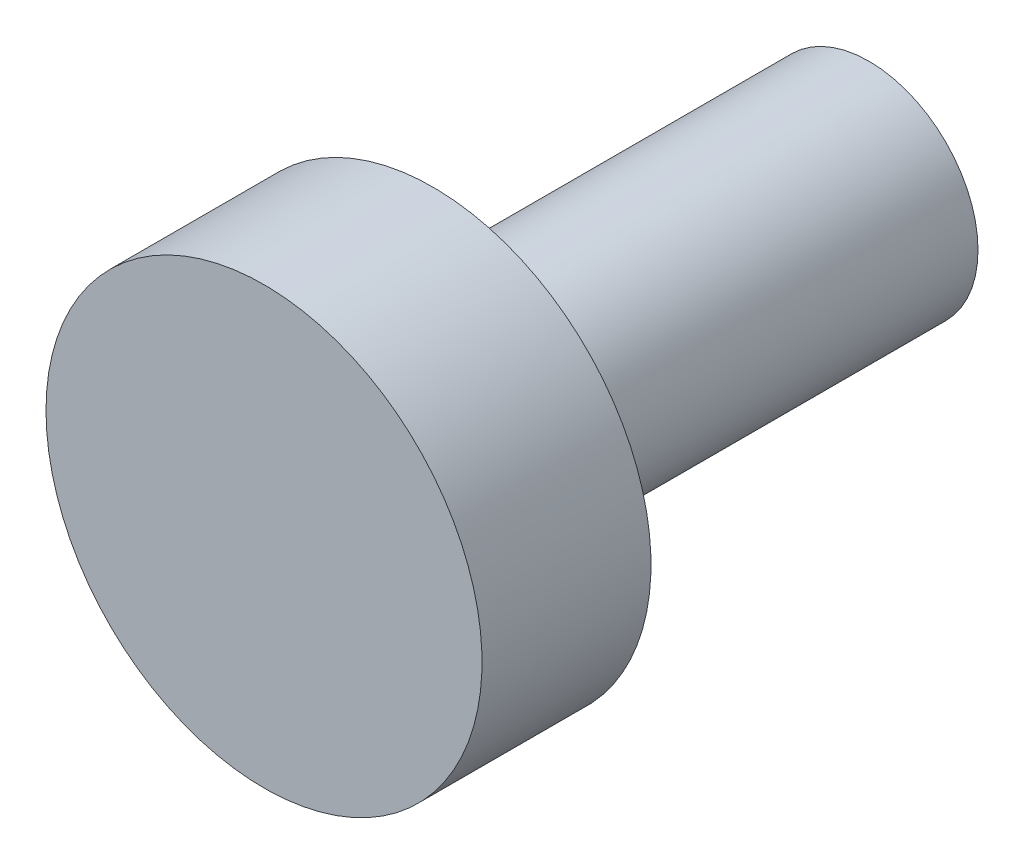
SolidWorks part; units mm, degrees
ref_plane "Plan de face" through (0, 0, 0) normal (0, 0, 1) x (1, 0, 0)
ref_plane "Plan de dessus" through (0, 0, 0) normal (0, 1, 0) x (1, 0, 0)
ref_plane "Plan de droite" through (0, 0, 0) normal (1, 0, 0) x (0, 0, -1)
sketch "Esquisse1" plane through (0, 0, 0) normal (0, 0, 1) x (1, 0, 0)
  circle A0 centre (0, 0) radius 4
  dimension "D1" = 8
extrude "Boss.-Extru.1" add sketch "Esquisse1" along normal blind 3.1
sketch "Esquisse2" plane through (0, 0, 0) normal (0, 0, -1) x (-1, 0, 0)
  circle A0 centre (0, 0) radius 2
  dimension "D1" = 4
extrude "Boss.-Extru.2" add sketch "Esquisse2" along normal blind 8
